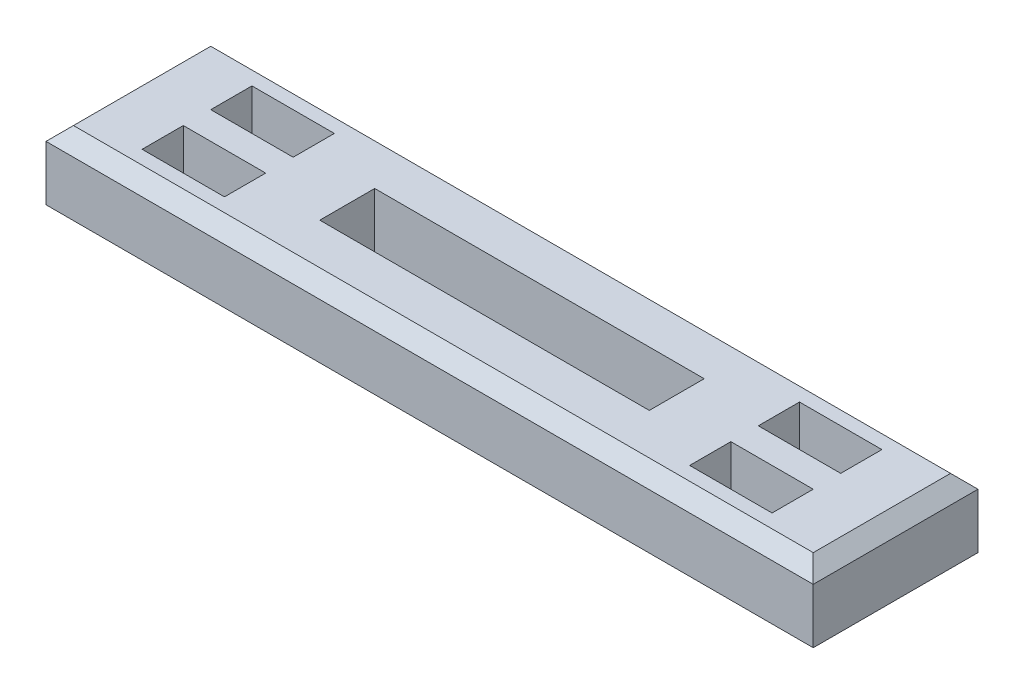
SolidWorks part; units mm, degrees
ref_plane "Спереди" through (0, 0, 0) normal (0, 0, 1) x (1, 0, 0)
ref_plane "Сверху" through (0, 0, 0) normal (0, 1, 0) x (1, 0, 0)
ref_plane "Справа" through (0, 0, 0) normal (1, 0, 0) x (0, 0, -1)
sketch "Эскиз1" plane through (0, 0, 0) normal (0, 0, 1) x (1, 0, 0)
  line L1 (-13.97, 1.5) -> (13.97, 1.5)
  line L2 (-13.97, 1.5) -> (-13.97, -1.5)
  line L3 (-13.97, -1.5) -> (13.97, -1.5)
  line L4 (13.97, 1.5) -> (13.97, -1.5)
  line L5 (-13.97, 1.5) -> (13.97, -1.5) construction
  line L6 (-13.97, -1.5) -> (13.97, 1.5) construction
  point P0 (0, 0)
  dimension "D1" = 27.94
  dimension "D2" = 3
extrude "Бобышка-Вытянуть2" add sketch "Эскиз1" along normal blind 6
sketch "Эскиз2" plane through (0, 1.5, 0) normal (0, 1, 0) x (1, 0, 0)
  line L0 (-13.97, -6) -> (-11.47, -6)
  line L1 (13.97, -6) -> (-13.97, -6) construction
  line L2 (-11.47, -6) -> (-11.47, 0)
  line L3 (13.97, 0) -> (-13.97, 0) construction
  line L4 (-11.47, 0) -> (-13.97, 0)
  line L5 (-13.97, 0) -> (-13.97, -6)
  line L6 (-11.47, -6) -> (-11.47, -5)
  line L7 (-11.47, -5) -> (-8.47, -5)
  line L8 (-8.47, -5) -> (-8.47, -3.5)
  line L9 (-8.47, -3.5) -> (-11.47, -3.5)
  line L10 (-11.47, -3.5) -> (-11.47, -2.5)
  line L11 (-11.47, -2.5) -> (-8.47, -2.5)
  line L12 (-8.47, -2.5) -> (-8.47, -1)
  line L13 (-8.47, -1) -> (-11.47, -1)
  line L14 (-11.47, -1) -> (-11.47, 0)
  line L15 (0, 0) -> (0, -6) construction
  line L16 (11.47, -1) -> (11.47, 0)
  line L17 (8.47, -1) -> (11.47, -1)
  line L18 (8.47, -2.5) -> (8.47, -1)
  line L19 (11.47, -2.5) -> (8.47, -2.5)
  line L20 (11.47, -3.5) -> (11.47, -2.5)
  line L21 (8.47, -3.5) -> (11.47, -3.5)
  line L22 (8.47, -5) -> (8.47, -3.5)
  line L23 (11.47, -5) -> (8.47, -5)
  line L24 (11.47, -6) -> (11.47, -5)
  line L25 (13.97, 0) -> (13.97, -6)
  line L26 (11.47, 0) -> (13.97, 0)
  line L27 (11.47, -6) -> (11.47, 0)
  line L28 (13.97, -6) -> (11.47, -6)
  dimension "D1" = 2.5
  dimension "D2" = 1
  dimension "D3" = 1.5
  dimension "D4" = 3
  dimension "D5" = 1
extrude "Вырез-Вытянуть1" cut sketch "Эскиз2" against normal blind 6 contours L12 L13 L2 L11 | L8 L9 L2 L7 | L23 L27 L21 L22 | L19 L27 L17 L18
chamfer "Фаска1" distance 0.5 angle 45 4 edges at (13.97, 1.5, 3) (0, 1.5, 6) (0, 1.5, 0) (-13.97, 1.5, 3)
chamfer "Фаска2" distance 0.5 angle 45 4 edges at (-13.97, -1.5, 3) (0, -1.5, 0) (13.97, -1.5, 3) (0, -1.5, 6)
sketch "Эскиз3" plane through (0, 1.5, 0) normal (0, 1, 0) x (1, 0, 0)
  line L0 (13.97, -3) -> (-13.97, -3) construction
  line L1 (13.97, 0) -> (13.97, -6) construction
  line L2 (-13.97, -6) -> (-13.97, 0) construction
  line L3 (0, -6) -> (0, 0) construction
  line L4 (13.97, -6) -> (-13.97, -6) construction
  line L5 (-13.97, 0) -> (13.97, 0) construction
  line L7 (6, -2) -> (-6, -2)
  line L8 (6, -2) -> (6, -4)
  line L9 (6, -4) -> (-6, -4)
  line L10 (-6, -2) -> (-6, -4)
  line L11 (6, -2) -> (-6, -4) construction
  line L12 (6, -4) -> (-6, -2) construction
  point P12 (0, -3)
  dimension "D1" = 2
  dimension "D2" = 12
extrude "Вырез-Вытянуть2" cut sketch "Эскиз3" against normal through all
